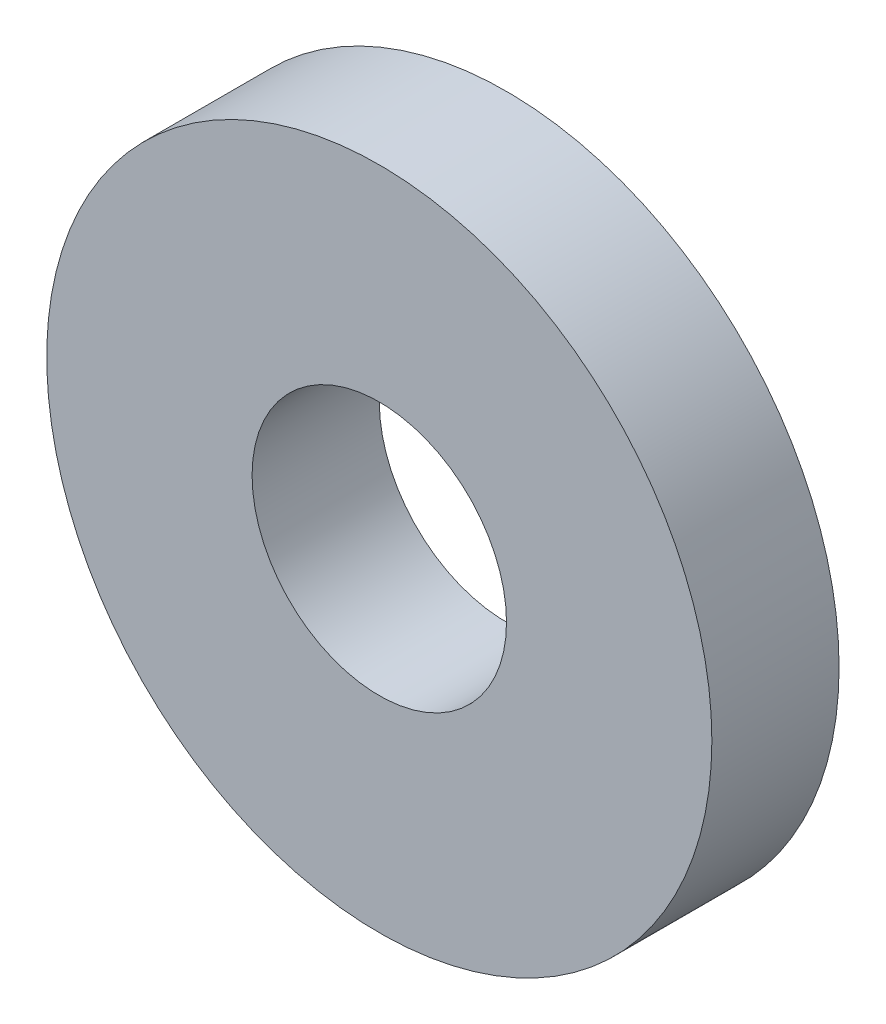
SolidWorks part; units mm, degrees
material "6061-T6 (SS)"
ref_plane "Front Plane" through (0, 0, 0) normal (0, 0, 1) x (1, 0, 0)
ref_plane "Top Plane" through (0, 0, 0) normal (0, 1, 0) x (1, 0, 0)
ref_plane "Right Plane" through (0, 0, 0) normal (1, 0, 0) x (0, 0, -1)
sketch "Sketch1" plane through (0, 0, 0) normal (0, 0, 1) x (1, 0, 0)
  circle A0 centre (8, 0) radius 1.5875
  circle A1 centre (8, 0) radius 4.15
  dimension "D1" = 8.3
extrude "Boss-Extrude1" add sketch "Sketch1" along normal blind 1.5875
